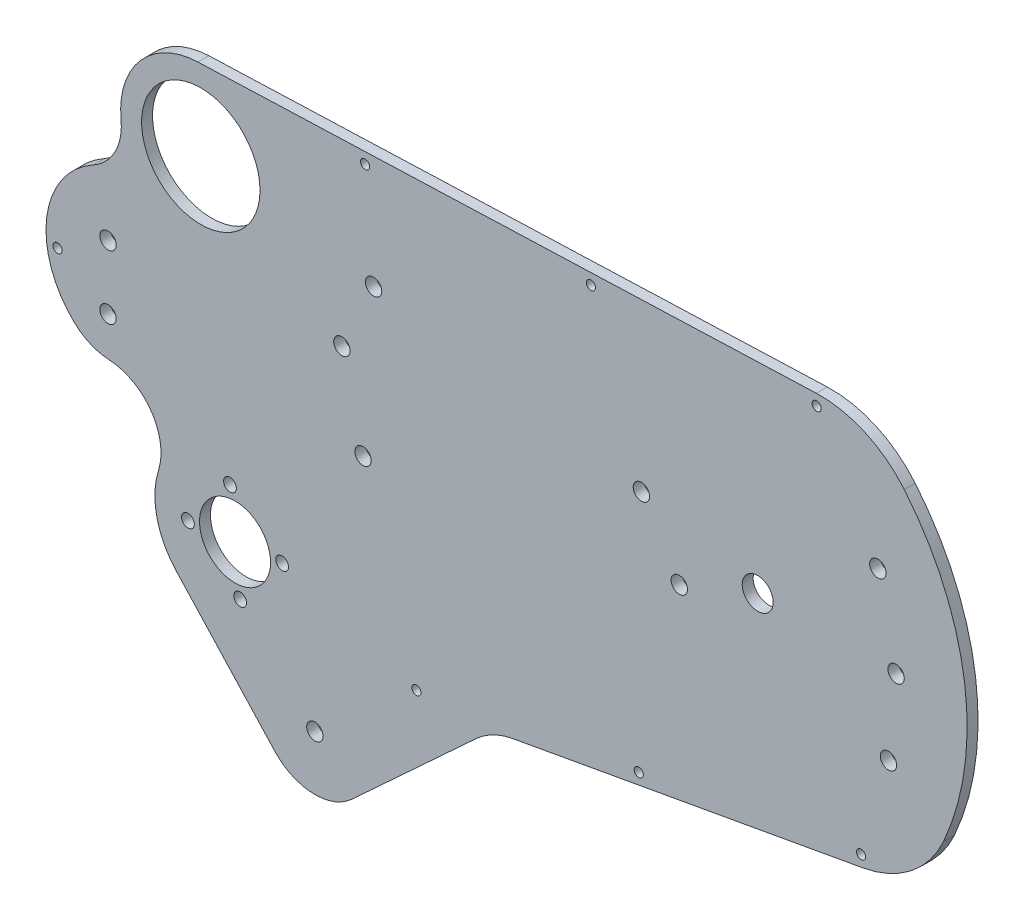
SolidWorks part; units mm, degrees
ref_plane "Front Plane" through (0, 0, 0) normal (0, 0, 1) x (1, 0, 0)
ref_plane "Top Plane" through (0, 0, 0) normal (0, 1, 0) x (1, 0, 0)
ref_plane "Right Plane" through (0, 0, 0) normal (1, 0, 0) x (0, 0, -1)
sketch "Sketch1" plane through (0, 0, 0) normal (0, 0, 1) x (1, 0, 0)
  line L0 (86.8854, -33.5) -> (-137.2004, -33.5) construction
  line L1 (-111.886, 49.4802) -> (83.0489, 41.2139) construction
  line L2 (-115.2069, 49.6211) -> (-101.035, -81.6153) construction
  line L3 (-97.8208, -80.7688) -> (92.1699, -30.731) construction
  line L4 (78.7977, 41.3942) -> (86.7407, -32.1609) construction
  line L5 (-108.121, -15.9971) -> (82.7692, 4.6166) construction
  line L6 (91, -33.5) -> (-88.5, -33.5) construction
  line L7 (-97.4673, 5.5) -> (-155.3054, 5.5) construction
  line L8 (-138.3, -14) -> (-155.3054, -14) construction
  line L9 (-138.3, 5.5) -> (-138.3, -33.5) construction
  line L10 (-155.3054, 5.5) -> (-155.3054, -33.5) construction
  line L11 (40.0178, 33.5) -> (40.0178, -33.5) construction
  line L12 (-101.0559, -81.4218) -> (-90.5433, -79.5278)
  line L13 (-91.5, 33.5) -> (88, 33.5) construction
  line L14 (-68.3, -21.5) -> (-107.0746, -25.6872) construction
  line L15 (-138.3, -5.25) -> (-81.5148, -93.5701) construction
  line L17 (-119.5948, -74.4106) -> (-92.5405, -103.7404)
  line L18 (-71.3446, -104.5958) -> (-37.2211, -73.1197)
  line L19 (-27.1401, -68.1042) -> (68.9251, -50.7959)
  line L20 (-115.1862, 49.4288) -> (56.0883, 55.6165)
  circle A0 centre (40.0178, 0) radius 4.25
  circle A1 centre (-112.8181, 27.5) radius 13 construction
  circle A2 centre (-103.4238, -59.4942) radius 13 construction
  arc A3 (-91.5, 33.5) -> (-88.5, -33.5) centre (-18.0922, 3.2198) ccw construction
  circle A4 centre (-68.3, -21.5) radius 2.25
  circle A6 centre (-138.3, -5.25) radius 2.25
  circle A7 centre (-138.3, -22.75) radius 2.25
  arc A8 (-142.3827, 10.6321) -> (-147.5429, -29.3643) centre (-130.3054, -11.2571) ccw
  arc A9 (-147.5429, -29.3643) -> (-137.2004, -33.5) centre (-137.2004, -18.5) ccw
  circle A10 centre (-112.8181, 27.5) radius 22
  arc A11 (68.9251, -50.7959) -> (91, -33.5) centre (63.6055, -21.2712) ccw
  circle A12 centre (-103.4238, -59.4942) radius 22
  arc A13 (91, -33.5) -> (80.2612, 44.7896) centre (22.6589, -2.9929) ccw
  arc A14 (91, -33.5) -> (88, 33.5) centre (22.6589, -2.9929) ccw construction
  arc A17 (-124.4228, -52.9336) -> (-137.9704, -33.4802) centre (-138.7403, -48.4604) ccw
  arc A18 (-142.3827, 10.6321) -> (-134.7058, 25.2795) centre (-149.6292, 23.7656) ccw
  circle A19 centre (-74.1, 1.7) radius 2.25
  circle A20 centre (-65.4, 20.2) radius 2.25
  circle A21 centre (8.1, 8.2) radius 2.25
  circle A23 centre (18.5, -8.7) radius 2.25
  circle A25 centre (78, -0.1) radius 2.25
  circle A26 centre (75.9, -21.8) radius 2.25
  circle A27 centre (73, 22.4) radius 2.25
  arc A28 (80.2612, 44.7896) -> (56.0883, 55.6165) centre (57.1714, 25.636) ccw
  circle A30 centre (-81.5148, -93.5701) radius 2.25
  circle A36 centre (-114.2138, 40.4249) radius 1.75
  circle A37 centre (-99.8933, 28.8957) radius 1.75
  circle A38 centre (-111.4224, 14.5751) radius 1.75
  circle A39 centre (-125.743, 26.1043) radius 1.75
  circle A40 centre (-104.8196, -46.5694) radius 1.75
  circle A41 centre (-90.499, -58.0985) radius 1.75
  circle A42 centre (-102.0281, -72.4191) radius 1.75
  circle A43 centre (-116.3487, -60.89) radius 1.75
  circle A44 centre (40.0178, 0) radius 35 construction
  circle A45 centre (40.0178, 0) radius 43
  circle A49 centre (-103.4238, -59.4942) radius 16.25
  circle A50 centre (-112.8181, 27.5) radius 16.25
  circle A51 centre (-112.8181, 27.5) radius 9.75
  circle A52 centre (-103.4238, -59.4942) radius 9.75
  arc A53 (91, -33.5) -> (88, 33.5) centre (22.6589, -2.9929) ccw construction
  arc A54 (-92.5405, -103.7404) -> (-71.3446, -104.5958) centre (-81.5148, -93.5701) ccw
  arc A55 (-27.1401, -68.1042) -> (-37.2211, -73.1197) centre (-23.5699, -87.9191) ccw
  circle A56 centre (-68.3, -21.5) radius 2.25 construction
  circle A57 centre (-74.1, 1.7) radius 2.25 construction
  circle A58 centre (-65.4, 20.2) radius 2.25 construction
  circle A59 centre (18.5, -8.7) radius 2.25 construction
  circle A60 centre (8.1, 8.2) radius 2.25 construction
  circle A61 centre (75.9, -21.8) radius 2.25 construction
  circle A62 centre (78, -0.1) radius 2.25 construction
  circle A63 centre (73, 22.4) radius 2.25 construction
  point P52 (82.7692, 4.6166)
  point P109 (-112.8181, 27.5)
  point P118 (-103.4238, -59.4942)
  dimension "D5" = 4.5
  dimension "D6" = 25
  dimension "D9" = 15
  dimension "D13" = 30
  dimension "D14" = 26
  dimension "D11" = 44
  dimension "D15" = 3.5
  dimension "D12" = 70
  dimension "D19" = 8.5
  dimension "D20" = 19.5
  dimension "D22" = 32.5
  dimension "D26" = 55
  dimension "D2" = 39
  dimension "D3" = 70
  dimension "D4" = 17.5
  dimension "D7" = 14
  dimension "D8" = 10
  dimension "D10" = 87.5
  dimension "D21" = 192
  dimension "D23" = 39
  dimension "D25" = 105
  dimension "D18" = 8
  dimension "D16" = 4
  dimension "D17" = 4
extrude "Boss-Extrude1" add sketch "Sketch1" along normal blind 3
sketch "Sketch2" plane through (0, 0, 3) normal (0, 0, 1) x (1, 0, 0)
  line L0 (68.3931, -47.8434) -> (7.3756, -58.8371) construction
  line L1 (-138.3, -5.25) -> (-138.3, -22.75) construction
  line L2 (7.3756, -58.8371) -> (-53.6419, -69.8308) construction
  line L7 (56.1966, 52.6184) -> (-113.5041, 46.4876)
  line L8 (56.1966, 52.6184) -> (-113.5041, 46.4876)
  line L9 (-67.7226, 48.1416) -> (-5.763, 50.38) construction
  line L10 (-5.763, 50.38) -> (56.1966, 52.6184) construction
  line L13 (-117.3897, -72.3766) -> (-90.3354, -101.7064)
  line L14 (-73.3786, -102.3907) -> (-39.2552, -70.9146)
  line L15 (-27.672, -65.1517) -> (68.3931, -47.8434)
  line L17 (-117.3897, -72.3766) -> (-90.3354, -101.7064) construction
  line L18 (-73.3786, -102.3907) -> (-39.2552, -70.9146) construction
  line L19 (-110.3186, -80.0424) -> (68.3931, -47.8434) construction
  circle A0 centre (7.3756, -58.8371) radius 1.25
  circle A2 centre (-53.6419, -69.8308) radius 1.25
  arc A14 (77.9522, 42.8742) -> (56.1966, 52.6184) centre (57.1714, 25.636) ccw
  arc A15 (77.9522, 42.8742) -> (56.1966, 52.6184) centre (57.1714, 25.636) ccw
  arc A16 (68.3931, -47.8434) -> (88.2606, -32.2771) centre (63.6055, -21.2712) ccw
  arc A17 (-114.7845, -75.2008) -> (-103.8362, -78.8745) centre (-105.964, -67.0646) ccw construction
  circle A21 centre (68.3931, -47.8434) radius 1.25
  circle A23 centre (56.1966, 52.6184) radius 1.25
  circle A24 centre (-5.763, 50.38) radius 1.25
  circle A27 centre (-67.7226, 48.1416) radius 1.25
  arc A28 (-113.5041, 46.4876) -> (-131.7211, 25.5823) centre (-112.8181, 27.5) ccw
  arc A29 (-140.9335, 8.0053) -> (-131.7211, 25.5823) centre (-149.6292, 23.7656) ccw
  arc A30 (-140.9335, 8.0053) -> (-145.4744, -27.1914) centre (-130.3054, -11.2571) ccw
  arc A31 (-145.4744, -27.1914) -> (-137.8164, -30.4842) centre (-137.2004, -18.5) ccw
  arc A32 (-121.5593, -53.8282) -> (-137.8164, -30.4842) centre (-138.7403, -48.4604) ccw
  arc A33 (-121.5593, -53.8282) -> (-117.3897, -72.3766) centre (-103.4238, -59.4942) ccw
  arc A34 (-90.3354, -101.7064) -> (-73.3786, -102.3907) centre (-81.5148, -93.5701) ccw
  arc A35 (-27.672, -65.1517) -> (-39.2552, -70.9146) centre (-23.5699, -87.9191) ccw
  arc A36 (88.2606, -32.2771) -> (77.9522, 42.8742) centre (22.6589, -2.9929) ccw
  arc A37 (-113.5041, 46.4876) -> (-131.7211, 25.5823) centre (-112.8181, 27.5) ccw construction
  arc A38 (-140.9335, 8.0053) -> (-131.7211, 25.5823) centre (-149.6292, 23.7656) ccw construction
  arc A39 (-140.9335, 8.0053) -> (-145.4744, -27.1914) centre (-130.3054, -11.2571) ccw construction
  arc A40 (-145.4744, -27.1914) -> (-137.8164, -30.4842) centre (-137.2004, -18.5) ccw construction
  arc A41 (-121.5593, -53.8282) -> (-137.8164, -30.4842) centre (-138.7403, -48.4604) ccw construction
  arc A42 (-121.5593, -53.8282) -> (-117.3897, -72.3766) centre (-103.4238, -59.4942) ccw construction
  arc A43 (-90.3354, -101.7064) -> (-73.3786, -102.3907) centre (-81.5148, -93.5701) ccw construction
  arc A44 (-27.672, -65.1517) -> (-39.2552, -70.9146) centre (-23.5699, -87.9191) ccw construction
  arc A45 (88.2606, -32.2771) -> (77.9522, 42.8742) centre (22.6589, -2.9929) ccw construction
  circle A47 centre (-152.1337, -14) radius 1.25
  arc A51 (68.3931, -47.8434) -> (88.2606, -32.2771) centre (63.6055, -21.2712) ccw
  point P2 (-138.3, -14)
  dimension "D4" = 2.5
  dimension "D2" = 62
  dimension "D1" = 3
extrude "Cut-Extrude1" cut sketch "Sketch2" against normal through all
